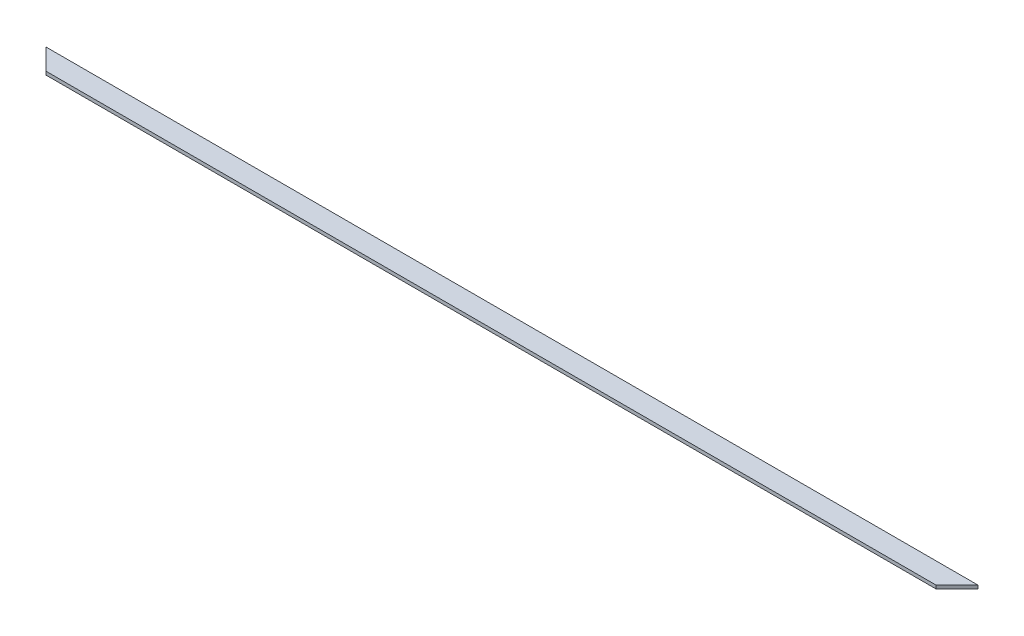
SolidWorks part; units mm, degrees
material "PE High Density"
ref_plane "Front Plane" through (0, 0, 0) normal (0, 0, 1) x (1, 0, 0)
ref_plane "Top Plane" through (0, 0, 0) normal (0, 1, 0) x (1, 0, 0)
ref_plane "Right Plane" through (0, 0, 0) normal (1, 0, 0) x (0, 0, -1)
sketch "Sketch1" plane through (0, 0, 0) normal (0, 1, 0) x (1, 0, 0)
  line L0 (-2569.2878, 921.398) -> (-2569.2878, 788.048) construction
  line L1 (-2702.6378, 921.398) -> (3228.2622, 921.398)
  line L2 (3094.9122, 921.398) -> (3094.9122, 788.048) construction
  line L3 (-2569.2878, 788.048) -> (3094.9122, 788.048)
  line L5 (-2702.6378, 921.398) -> (-2569.2878, 788.048)
  line L6 (3228.2622, 921.398) -> (3094.9122, 788.048)
  dimension "D1" = 5930.9
  dimension "D2" = 133.35
  dimension "D3" = 133.35
extrude "Boss-Extrude1" add sketch "Sketch1" along normal blind 21.59 contours L3 L6 L1 L5
